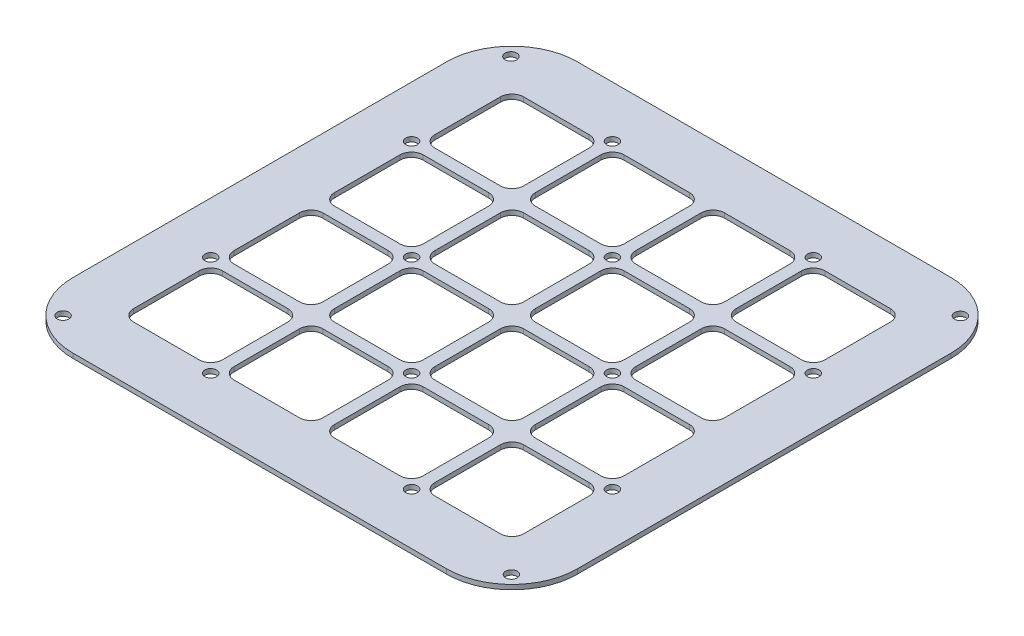
SolidWorks part; units mm, degrees
ref_plane "Front Plane" through (0, 0, 0) normal (0, 0, 1) x (1, 0, 0)
ref_plane "Top Plane" through (0, 0, 0) normal (0, 1, 0) x (1, 0, 0)
ref_plane "Right Plane" through (0, 0, 0) normal (1, 0, 0) x (0, 0, -1)
sketch "Sketch1" plane through (0, 0, 0) normal (0, 1, 0) x (1, 0, 0)
  line L0 (-35.5, 83.6244) -> (-7.5, 83.6244)
  line L1 (-40.5, 78.6244) -> (-40.5, 50.6244)
  line L2 (-35.5, 45.6244) -> (-7.5, 45.6244)
  line L3 (-2.5, 78.6244) -> (-2.5, 50.6244)
  line L4 (7.5, 83.6244) -> (35.5, 83.6244)
  line L5 (-78.5, 83.6244) -> (-50.5, 83.6244)
  line L6 (-83.5, 78.6244) -> (-83.5, 50.6244)
  line L7 (-78.5, 45.6244) -> (-50.5, 45.6244)
  line L8 (-45.5, 78.6244) -> (-45.5, 50.6244)
  line L9 (2.5, 78.6244) -> (2.5, 50.6244)
  line L10 (7.5, 45.6244) -> (35.5, 45.6244)
  line L11 (40.5, 78.6244) -> (40.5, 50.6244)
  line L12 (50.5, 83.6244) -> (78.5, 83.6244)
  line L13 (45.5, 78.6244) -> (45.5, 50.6244)
  line L14 (50.5, 45.6244) -> (78.5, 45.6244)
  line L15 (83.5, 78.6244) -> (83.5, 50.6244)
  line L16 (-35.5, 40.6244) -> (-7.5, 40.6244)
  line L17 (-40.5, 35.6244) -> (-40.5, 7.6244)
  line L18 (-35.5, 2.6244) -> (-7.5, 2.6244)
  line L19 (-2.5, 35.6244) -> (-2.5, 7.6244)
  line L20 (7.5, 40.6244) -> (35.5, 40.6244)
  line L21 (2.5, 35.6244) -> (2.5, 7.6244)
  line L22 (7.5, 2.6244) -> (35.5, 2.6244)
  line L23 (40.5, 35.6244) -> (40.5, 7.6244)
  line L24 (50.5, 40.6244) -> (78.5, 40.6244)
  line L25 (45.5, 35.6244) -> (45.5, 7.6244)
  line L26 (50.5, 2.6244) -> (78.5, 2.6244)
  line L27 (83.5, 35.6244) -> (83.5, 7.6244)
  line L28 (-35.5, -2.3756) -> (-7.5, -2.3756)
  line L29 (-40.5, -7.3756) -> (-40.5, -35.3756)
  line L30 (-35.5, -40.3756) -> (-7.5, -40.3756)
  line L31 (-2.5, -7.3756) -> (-2.5, -35.3756)
  line L32 (7.5, -2.3756) -> (35.5, -2.3756)
  line L33 (2.5, -7.3756) -> (2.5, -35.3756)
  line L34 (7.5, -40.3756) -> (35.5, -40.3756)
  line L35 (40.5, -7.3756) -> (40.5, -35.3756)
  line L36 (50.5, -2.3756) -> (78.5, -2.3756)
  line L37 (45.5, -7.3756) -> (45.5, -35.3756)
  line L38 (50.5, -40.3756) -> (78.5, -40.3756)
  line L39 (83.5, -7.3756) -> (83.5, -35.3756)
  line L40 (-35.5, -45.3756) -> (-7.5, -45.3756)
  line L41 (-40.5, -50.3756) -> (-40.5, -78.3756)
  line L42 (-35.5, -83.3756) -> (-7.5, -83.3756)
  line L43 (-2.5, -50.3756) -> (-2.5, -78.3756)
  line L44 (7.5, -45.3756) -> (35.5, -45.3756)
  line L45 (2.5, -50.3756) -> (2.5, -78.3756)
  line L46 (7.5, -83.3756) -> (35.5, -83.3756)
  line L47 (40.5, -50.3756) -> (40.5, -78.3756)
  line L48 (50.5, -45.3756) -> (78.5, -45.3756)
  line L49 (45.5, -50.3756) -> (45.5, -78.3756)
  line L50 (50.5, -83.3756) -> (78.5, -83.3756)
  line L51 (83.5, -50.3756) -> (83.5, -78.3756)
  line L52 (-78.5, 40.6244) -> (-50.5, 40.6244)
  line L53 (-83.5, 35.6244) -> (-83.5, 7.6244)
  line L54 (-78.5, 2.6244) -> (-50.5, 2.6244)
  line L55 (-45.5, 35.6244) -> (-45.5, 7.6244)
  line L56 (-78.5, -2.3756) -> (-50.5, -2.3756)
  line L57 (-83.5, -7.3756) -> (-83.5, -35.3756)
  line L58 (-78.5, -40.3756) -> (-50.5, -40.3756)
  line L59 (-45.5, -7.3756) -> (-45.5, -35.3756)
  line L60 (-78.5, -45.3756) -> (-50.5, -45.3756)
  line L61 (-83.5, -50.3756) -> (-83.5, -78.3756)
  line L62 (-78.5, -83.3756) -> (-50.5, -83.3756)
  line L63 (-45.5, -50.3756) -> (-45.5, -78.3756)
  line L64 (83.5, 64.6244) -> (-83.5, 64.6244) construction
  line L65 (83.5, 21.6244) -> (-83.5, 21.6244) construction
  line L66 (83.5, -21.3756) -> (-83.5, -21.3756) construction
  line L67 (83.5, -64.3756) -> (-83.5, -64.3756) construction
  line L68 (64.5, 83.6244) -> (64.5, -83.3756) construction
  line L69 (21.5, 83.6244) -> (21.5, -83.3756) construction
  line L70 (-21.5, 83.6244) -> (-21.5, -83.3756) construction
  line L71 (-64.5, 83.6244) -> (-64.5, -83.3756) construction
  line L72 (80, 108.1244) -> (-80, 108.1244)
  line L73 (-108, 80.1244) -> (-108, 70.1244)
  line L74 (-108, -79.8756) -> (-108, 70.1244)
  line L75 (-80, -107.8756) -> (80, -107.8756)
  line L76 (108, -79.8756) -> (108, 70.1244)
  line L77 (108, 70.1244) -> (108, 80.1244)
  arc A0 (-45.5, 78.6244) -> (-50.5, 83.6244) centre (-50.5, 78.6244) ccw
  arc A1 (-83.5, 78.6244) -> (-78.5, 83.6244) centre (-78.5, 78.6244) cw
  arc A2 (-78.5, 45.6244) -> (-83.5, 50.6244) centre (-78.5, 50.6244) cw
  arc A3 (-45.5, 50.6244) -> (-50.5, 45.6244) centre (-50.5, 50.6244) cw
  arc A4 (-40.5, 78.6244) -> (-35.5, 83.6244) centre (-35.5, 78.6244) cw
  arc A5 (-35.5, 45.6244) -> (-40.5, 50.6244) centre (-35.5, 50.6244) cw
  arc A6 (-2.5, 50.6244) -> (-7.5, 45.6244) centre (-7.5, 50.6244) cw
  arc A7 (-2.5, 78.6244) -> (-7.5, 83.6244) centre (-7.5, 78.6244) ccw
  arc A8 (2.5, 78.6244) -> (7.5, 83.6244) centre (7.5, 78.6244) cw
  arc A9 (7.5, 45.6244) -> (2.5, 50.6244) centre (7.5, 50.6244) cw
  arc A10 (40.5, 50.6244) -> (35.5, 45.6244) centre (35.5, 50.6244) cw
  arc A11 (40.5, 78.6244) -> (35.5, 83.6244) centre (35.5, 78.6244) ccw
  arc A12 (45.5, 78.6244) -> (50.5, 83.6244) centre (50.5, 78.6244) cw
  arc A13 (50.5, 45.6244) -> (45.5, 50.6244) centre (50.5, 50.6244) cw
  arc A14 (83.5, 50.6244) -> (78.5, 45.6244) centre (78.5, 50.6244) cw
  arc A15 (83.5, 78.6244) -> (78.5, 83.6244) centre (78.5, 78.6244) ccw
  arc A16 (-40.5, 35.6244) -> (-35.5, 40.6244) centre (-35.5, 35.6244) cw
  arc A17 (-35.5, 2.6244) -> (-40.5, 7.6244) centre (-35.5, 7.6244) cw
  arc A18 (-2.5, 7.6244) -> (-7.5, 2.6244) centre (-7.5, 7.6244) cw
  arc A19 (-2.5, 35.6244) -> (-7.5, 40.6244) centre (-7.5, 35.6244) ccw
  arc A20 (2.5, 35.6244) -> (7.5, 40.6244) centre (7.5, 35.6244) cw
  arc A21 (7.5, 2.6244) -> (2.5, 7.6244) centre (7.5, 7.6244) cw
  arc A22 (40.5, 7.6244) -> (35.5, 2.6244) centre (35.5, 7.6244) cw
  arc A23 (40.5, 35.6244) -> (35.5, 40.6244) centre (35.5, 35.6244) ccw
  arc A24 (45.5, 35.6244) -> (50.5, 40.6244) centre (50.5, 35.6244) cw
  arc A25 (50.5, 2.6244) -> (45.5, 7.6244) centre (50.5, 7.6244) cw
  arc A26 (83.5, 7.6244) -> (78.5, 2.6244) centre (78.5, 7.6244) cw
  arc A27 (83.5, 35.6244) -> (78.5, 40.6244) centre (78.5, 35.6244) ccw
  arc A28 (-40.5, -7.3756) -> (-35.5, -2.3756) centre (-35.5, -7.3756) cw
  arc A29 (-35.5, -40.3756) -> (-40.5, -35.3756) centre (-35.5, -35.3756) cw
  arc A30 (-2.5, -35.3756) -> (-7.5, -40.3756) centre (-7.5, -35.3756) cw
  arc A31 (-2.5, -7.3756) -> (-7.5, -2.3756) centre (-7.5, -7.3756) ccw
  arc A32 (2.5, -7.3756) -> (7.5, -2.3756) centre (7.5, -7.3756) cw
  arc A33 (7.5, -40.3756) -> (2.5, -35.3756) centre (7.5, -35.3756) cw
  arc A34 (40.5, -35.3756) -> (35.5, -40.3756) centre (35.5, -35.3756) cw
  arc A35 (40.5, -7.3756) -> (35.5, -2.3756) centre (35.5, -7.3756) ccw
  arc A36 (45.5, -7.3756) -> (50.5, -2.3756) centre (50.5, -7.3756) cw
  arc A37 (50.5, -40.3756) -> (45.5, -35.3756) centre (50.5, -35.3756) cw
  arc A38 (83.5, -35.3756) -> (78.5, -40.3756) centre (78.5, -35.3756) cw
  arc A39 (83.5, -7.3756) -> (78.5, -2.3756) centre (78.5, -7.3756) ccw
  arc A40 (-40.5, -50.3756) -> (-35.5, -45.3756) centre (-35.5, -50.3756) cw
  arc A41 (-35.5, -83.3756) -> (-40.5, -78.3756) centre (-35.5, -78.3756) cw
  arc A42 (-2.5, -78.3756) -> (-7.5, -83.3756) centre (-7.5, -78.3756) cw
  arc A43 (-2.5, -50.3756) -> (-7.5, -45.3756) centre (-7.5, -50.3756) ccw
  arc A44 (2.5, -50.3756) -> (7.5, -45.3756) centre (7.5, -50.3756) cw
  arc A45 (7.5, -83.3756) -> (2.5, -78.3756) centre (7.5, -78.3756) cw
  arc A46 (40.5, -78.3756) -> (35.5, -83.3756) centre (35.5, -78.3756) cw
  arc A47 (40.5, -50.3756) -> (35.5, -45.3756) centre (35.5, -50.3756) ccw
  arc A48 (45.5, -50.3756) -> (50.5, -45.3756) centre (50.5, -50.3756) cw
  arc A49 (50.5, -83.3756) -> (45.5, -78.3756) centre (50.5, -78.3756) cw
  arc A50 (83.5, -78.3756) -> (78.5, -83.3756) centre (78.5, -78.3756) cw
  arc A51 (83.5, -50.3756) -> (78.5, -45.3756) centre (78.5, -50.3756) ccw
  arc A52 (-83.5, 35.6244) -> (-78.5, 40.6244) centre (-78.5, 35.6244) cw
  arc A53 (-78.5, 2.6244) -> (-83.5, 7.6244) centre (-78.5, 7.6244) cw
  arc A54 (-45.5, 7.6244) -> (-50.5, 2.6244) centre (-50.5, 7.6244) cw
  arc A55 (-45.5, 35.6244) -> (-50.5, 40.6244) centre (-50.5, 35.6244) ccw
  arc A56 (-83.5, -7.3756) -> (-78.5, -2.3756) centre (-78.5, -7.3756) cw
  arc A57 (-78.5, -40.3756) -> (-83.5, -35.3756) centre (-78.5, -35.3756) cw
  arc A58 (-45.5, -35.3756) -> (-50.5, -40.3756) centre (-50.5, -35.3756) cw
  arc A59 (-45.5, -7.3756) -> (-50.5, -2.3756) centre (-50.5, -7.3756) ccw
  arc A60 (-83.5, -50.3756) -> (-78.5, -45.3756) centre (-78.5, -50.3756) cw
  arc A61 (-78.5, -83.3756) -> (-83.5, -78.3756) centre (-78.5, -78.3756) cw
  arc A62 (-45.5, -78.3756) -> (-50.5, -83.3756) centre (-50.5, -78.3756) cw
  arc A63 (-45.5, -50.3756) -> (-50.5, -45.3756) centre (-50.5, -50.3756) ccw
  arc A64 (-80, 108.1244) -> (-108, 80.1244) centre (-80, 80.1244) ccw
  arc A65 (108, 80.1244) -> (80, 108.1244) centre (80, 80.1244) ccw
  arc A66 (108, -79.8756) -> (80, -107.8756) centre (80, -79.8756) cw
  arc A67 (-80, -107.8756) -> (-108, -79.8756) centre (-80, -79.8756) cw
  dimension "D1" = 5
  dimension "D2" = 5
  dimension "D3" = 5
  dimension "D4" = 5
  dimension "D10" = 28
  dimension "D11" = 28
  dimension "D5" = 38
  dimension "D6" = 5
  dimension "D7" = 5
  dimension "D8" = 24.5
  dimension "D9" = 24.5
  dimension "D12" = 216
extrude "Boss-Extrude1" add sketch "Sketch1" along normal blind 2
sketch "Sketch2" plane through (0, 0, 0) normal (0, -1, 0) x (1, 0, 0)
  line L0 (-108, -0.1244) -> (108, -0.1244)
  line L1 (-108, -80.1244) -> (-108, 79.8756) construction
  line L2 (108, 79.8756) -> (108, -80.1244) construction
  line L3 (0, 107.8756) -> (0, -108.1244)
  line L4 (-80, 107.8756) -> (80, 107.8756) construction
  line L5 (80, -108.1244) -> (-80, -108.1244) construction
  line L7 (-43, 107.8756) -> (-43, -108.1244) construction
  line L10 (43, 107.8756) -> (43, -108.1244) construction
  line L11 (108, 42.8756) -> (-108, 42.8756) construction
  line L12 (108, -43.1244) -> (-108, -43.1244) construction
  line L13 (-35.5, -45.6244) -> (-7.5, -45.6244) construction
  line L14 (45.5, -35.6244) -> (45.5, -7.6244) construction
  line L15 (-40.5, -35.6244) -> (-40.5, -7.6244) construction
  line L16 (-7.5, 45.3756) -> (-35.5, 45.3756) construction
  line L17 (-107.3496, 85.8756) -> (107.3496, 85.8756) construction
  line L18 (-86, 107.2252) -> (-86, -107.4739) construction
  line L19 (-107.3496, -86.1244) -> (107.3496, -86.1244) construction
  line L20 (86, 107.2252) -> (86, -107.4739) construction
  arc A26 (-80, 107.8756) -> (-108, 79.8756) centre (-80, 79.8756) ccw construction
  arc A27 (108, 79.8756) -> (80, 107.8756) centre (80, 79.8756) ccw construction
  arc A28 (-108, -80.1244) -> (-80, -108.1244) centre (-80, -80.1244) ccw construction
  arc A29 (80, -108.1244) -> (108, -80.1244) centre (80, -80.1244) ccw construction
  circle A30 centre (-43, 85.8756) radius 2.5
  circle A31 centre (-86, 42.8756) radius 2.5
  circle A32 centre (-43, -0.1244) radius 2.5
  circle A33 centre (0, 42.8756) radius 2.5
  circle A34 centre (43, -0.1244) radius 2.5
  circle A35 centre (86, 42.8756) radius 2.5
  circle A36 centre (43, 85.8756) radius 2.5
  circle A37 centre (86, -43.1244) radius 2.5
  circle A38 centre (43, -86.1244) radius 2.5
  circle A39 centre (0, -43.1244) radius 2.5
  circle A40 centre (-43, -86.1244) radius 2.5
  circle A41 centre (-86, -43.1244) radius 2.5
  circle A42 centre (-86, 42.8756) radius 3.5
  circle A43 centre (-43, 85.8756) radius 3.5
  circle A44 centre (0, 42.8756) radius 3.5
  circle A45 centre (-43, -0.1244) radius 3.5
  circle A46 centre (43, -0.1244) radius 3.5
  circle A47 centre (43, 85.8756) radius 3.5
  circle A48 centre (86, 42.8756) radius 3.5
  circle A49 centre (86, -43.1244) radius 3.5
  circle A50 centre (43, -86.1244) radius 3.5
  circle A51 centre (-43, -86.1244) radius 3.5
  circle A52 centre (0, -43.1244) radius 3.5
  circle A53 centre (-86, -43.1244) radius 3.5
  dimension "D2" = 2.5
  dimension "D3" = 2.5
  dimension "D5" = 43
  dimension "D6" = 43
  dimension "D8" = 43
  dimension "D9" = 5
  dimension "D10" = 5
  dimension "D11" = 43
  dimension "D12" = 5
  dimension "D13" = 5
  dimension "D14" = 7
  dimension "D15" = 7
  dimension "D16" = 7
  dimension "D17" = 7
  dimension "D1" = 2.5
  dimension "D4" = 2.5
  dimension "D7" = 43
sketch "Sketch3" plane through (0, 0, 0) normal (0, -1, 0) x (1, 0, 0)
  line L0 (-108, 0.1244) -> (108, -0.1244)
  line L1 (108, 79.8756) -> (108, -80.1244) construction
  line L2 (0, -107.8756) -> (0, 107.8756)
  line L3 (-80, 107.8756) -> (80, 107.8756) construction
  circle A0 centre (-96, 96.1106) radius 2.5
  circle A1 centre (-96, 96.1106) radius 3.5
  circle A2 centre (-96.2211, -95.8893) radius 3.5
  circle A3 centre (-96.2211, -95.8893) radius 2.5
  circle A4 centre (96.2211, -95.8893) radius 3.5
  circle A5 centre (96.2211, -95.8893) radius 2.5
  circle A6 centre (96, 96.1106) radius 3.5
  circle A7 centre (96, 96.1106) radius 2.5
  point P6 (0, 0)
  point P12 (0, 0)
  dimension "D1" = 5
  dimension "D2" = 7
  dimension "D3" = 96
  dimension "D4" = 96
extrude "Cut-Extrude1" cut sketch "Sketch2" against normal up to next
extrude "Cut-Extrude3" cut sketch "Sketch3" against normal up to next contours A0 | A7 | A5 | A3
